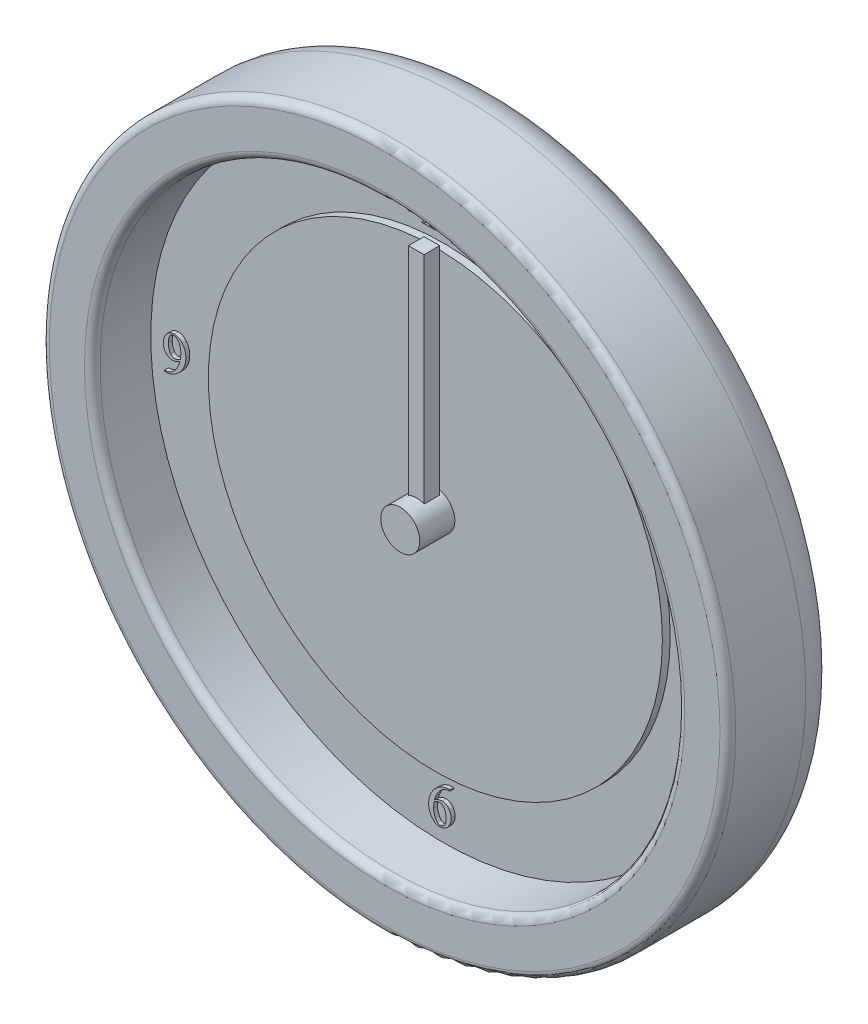
SolidWorks part; units mm, degrees
ref_plane "Front Plane" through (0, 0, 0) normal (0, 0, 1) x (1, 0, 0)
ref_plane "Top Plane" through (0, 0, 0) normal (0, 1, 0) x (1, 0, 0)
ref_plane "Right Plane" through (0, 0, 0) normal (1, 0, 0) x (0, 0, -1)
sketch "Sketch1" plane through (0, 0, 0) normal (0, 0, 1) x (1, 0, 0)
  circle A0 centre (0, 0) radius 111.76
  dimension "D1" = 223.52
extrude "Boss-Extrude1" add sketch "Sketch1" along normal blind 38.1
sketch "Sketch2" plane through (0, 0, 38.1) normal (0, 0, 1) x (1, 0, 0)
  circle A0 centre (0, 0) radius 95.25
  dimension "D1" = 190.5
extrude "Cut-Extrude1" cut sketch "Sketch2" against normal blind 19.05
fillet "Fillet1" radius 2.54 1 edges at (95.25, 0, 38.1)
fillet "Fillet2" radius 2.54 1 edges at (111.76, 0, 38.1)
fillet "Fillet3" radius 12.7 1 edges at (111.76, 0, 0)
sketch "Sketch3" plane through (0, 0, 0) normal (0, 0, 1) x (1, 0, 0)
  line L0 (0, 0) -> (0, 95.25) construction
  line L1 (0, 0) -> (47.625, 82.4889) construction
  line L2 (0, 0) -> (82.4889, 47.625) construction
  line L3 (0, 0) -> (95.25, 0) construction
  line L4 (0, 0) -> (82.4889, -47.625) construction
  line L5 (0, 0) -> (47.625, -82.4889) construction
  line L6 (0, 0) -> (0, -95.25) construction
  line L7 (0, 0) -> (-47.625, -82.4889) construction
  line L8 (0, 0) -> (-82.4889, -47.625) construction
  line L9 (0, 0) -> (-95.25, 0) construction
  line L10 (0, 0) -> (-82.4889, 47.625) construction
  line L11 (0, 0) -> (-47.625, 82.4889) construction
  circle A0 centre (0, 0) radius 95.25 construction
  circle A1 centre (0, 0) radius 95.25 construction
  text T0 "12" font "Times New Roman" height in points 48
  text T1 "3" font "Times New Roman" height in points 48
  text T2 "9" font "Times New Roman" height in points 48
  text T3 "6" font "Times New Roman" height in points 48
  point P20 (0, 0)
  dimension "D1" = 12
extrude "Boss-Extrude7" add sketch "Sketch3" along normal blind 20.32
sketch "Sketch4" plane through (0, 0, 19.05) normal (0, 0, 1) x (1, 0, 0)
  circle A0 centre (0, 0) radius 6.35
  dimension "D1" = 12.7
extrude "Boss-Extrude8" add sketch "Sketch4" along normal blind 13.97
sketch "Sketch5" plane through (0, 0, 19.05) normal (0, 0, 1) x (1, 0, 0)
  circle A0 centre (0, 0) radius 73.9432
extrude "Boss-Extrude9" add sketch "Sketch5" along normal blind 2.54
sketch "Sketch6" plane through (0, 0, 0) normal (0, 1, 0) x (1, 0, 0)
  line L1 (2.4785, -27.7434) -> (-2.6015, -27.7434)
  line L2 (2.4785, -27.7434) -> (2.4785, -22.6634)
  line L3 (2.4785, -22.6634) -> (-2.6015, -22.6634)
  line L4 (-2.6015, -27.7434) -> (-2.6015, -22.6634)
  line L5 (2.4785, -27.7434) -> (-2.6015, -22.6634) construction
  line L6 (2.4785, -22.6634) -> (-2.6015, -27.7434) construction
  point P0 (-0.0615, -25.2034)
  dimension "D1" = 5.08
  dimension "D2" = 5.08
extrude "Boss-Extrude12" add sketch "Sketch6" along normal blind 76.2
